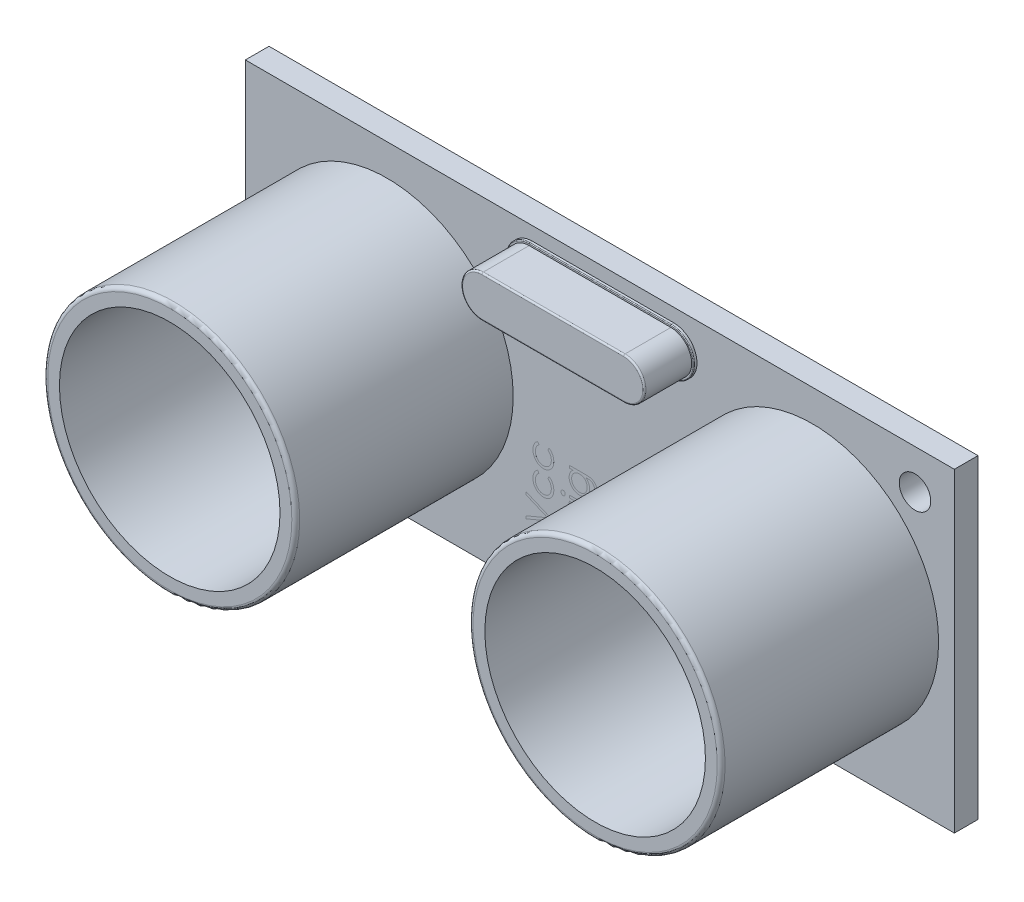
SolidWorks part; units mm, degrees
ref_plane "Front Plane" through (0, 0, 0) normal (0, 0, 1) x (1, 0, 0)
ref_plane "Top Plane" through (0, 0, 0) normal (0, 1, 0) x (1, 0, 0)
ref_plane "Right Plane" through (0, 0, 0) normal (1, 0, 0) x (0, 0, -1)
sketch "Sketch1" plane through (0, 0, 0) normal (0, 0, 1) x (1, 0, 0)
  line L1 (0, 0) -> (45, 0)
  line L2 (0, 0) -> (0, 20)
  line L3 (0, 20) -> (45, 20)
  line L4 (45, 0) -> (45, 20)
  circle A0 centre (2.5, 2.5) radius 1
  circle A1 centre (42.5, 17.5) radius 1
  dimension "D3" = 2
  dimension "D4" = 2
  dimension "D5" = 15
  dimension "D6" = 2.5
  dimension "D7" = 2.5
  dimension "D8" = 40
  dimension "D1" = 20
  dimension "D2" = 45
extrude "Boss-Extrude1" add sketch "Sketch1" along normal blind 1.5
sketch "Sketch2" plane through (0, 0, 1.5) normal (0, 0, 1) x (1, 0, 0)
  line L0 (0, 20) -> (0, 0) construction
  line L1 (45, 20) -> (0, 20) construction
  circle A0 centre (9, 10) radius 8
  circle A1 centre (36, 10) radius 8
  dimension "D1" = 16
  dimension "D2" = 16
  dimension "D3" = 27
  dimension "D4" = 9
  dimension "D5" = 10
  dimension "D6" = 10
extrude "Boss-Extrude2" add sketch "Sketch2" along normal blind 13.8
sketch "Sketch3" plane through (0, 0, 15.3) normal (0, 0, 1) x (1, 0, 0)
  circle A0 centre (9, 10) radius 7
  circle A1 centre (36, 10) radius 7
  circle A2 centre (36, 10) radius 8 construction
  dimension "D1" = 14
  dimension "D2" = 14
  dimension "D3" = 0
extrude "Cut-Extrude1" cut sketch "Sketch3" against normal blind 11
sketch "Sketch4" plane through (0, 0, 4.3) normal (0, 0, 1) x (1, 0, 0)
  circle A0 centre (9, 10) radius 6
  circle A1 centre (36, 10) radius 6
  circle A2 centre (36, 10) radius 7 construction
  dimension "D1" = 12
  dimension "D2" = 12
  dimension "D3" = 0
extrude "Boss-Extrude3" add sketch "Sketch4" along normal blind 1
fillet "Fillet1" radius 0.25 2 edges at (44, 10, 15.3) (17, 10, 15.3)
sketch "Sketch6" plane through (0, 0, 1.5) normal (0, 0, 1) x (1, 0, 0)
  line L0 (18.2127, 17.6702) -> (27.1892, 17.6702) construction
  line L1 (18.2127, 19.1439) -> (27.1892, 19.1439)
  line L2 (18.2127, 16.1964) -> (27.1892, 16.1964)
  arc A0 (18.2127, 19.1439) -> (18.2127, 16.1964) centre (18.2127, 17.6702) ccw
  arc A1 (27.1892, 16.1964) -> (27.1892, 19.1439) centre (27.1892, 17.6702) ccw
  point P2 (22.701, 17.6702)
extrude "Boss-Extrude4" add sketch "Sketch6" along normal blind 0.2
sketch "Sketch7" plane through (0, 0, 1.7) normal (0, 0, 1) x (1, 0, 0)
  line L0 (18.2101, 17.6795) -> (27.2081, 17.6795) construction
  line L1 (18.2101, 18.9989) -> (27.2081, 18.9989)
  line L2 (18.2101, 16.3602) -> (27.2081, 16.3602)
  arc A0 (18.2101, 18.9989) -> (18.2101, 16.3602) centre (18.2101, 17.6795) ccw
  arc A1 (27.2081, 16.3602) -> (27.2081, 18.9989) centre (27.2081, 17.6795) ccw
  point P2 (22.7091, 17.6795)
extrude "Boss-Extrude5" add sketch "Sketch7" along normal blind 3
fillet "Fillet2" radius 0.1 4 edges at (16.8908, 17.6795, 4.7) (22.7091, 18.9989, 4.7) (28.5274, 17.6795, 4.7) (22.7091, 16.3602, 4.7)
fillet "Fillet3" radius 0.05 4 edges at (28.6629, 17.6702, 1.7) (22.701, 16.1964, 1.7) (16.739, 17.6702, 1.7) (22.701, 19.1439, 1.7)
sketch "Sketch9" plane through (0, 0, 0) normal (0, 0, -1) x (-1, 0, 0)
  line L1 (0, 0) -> (-45, 0) construction
  circle A0 centre (-26.31, 2.5) radius 0.635
  circle A1 centre (-23.77, 2.5) radius 0.635
  circle A2 centre (-21.23, 2.5) radius 0.635
  circle A3 centre (-18.69, 2.5) radius 0.635
  point P10 (-22.5, 0)
  dimension "D1" = 1.27
  dimension "D2" = 1.27
  dimension "D3" = 1.27
  dimension "D4" = 1.27
  dimension "D5" = 2.5
  dimension "D6" = 2.54
  dimension "D7" = 2.54
  dimension "D8" = 2.54
  dimension "D9" = 2.5
  dimension "D10" = 2.5
  dimension "D11" = 2.5
  dimension "D12" = 1.27
extrude "Boss-Extrude6" add sketch "Sketch9" along normal blind 4 and the other way blind 2
sketch "Sketch10" plane through (0, 0, 1.5) normal (0, 0, 1) x (1, 0, 0)
  line L0 (19.5534, 3.5859) -> (19.5534, 8.1823) construction
  line L1 (21.8515, 8.1823) -> (21.8515, 3.5859) construction
  line L2 (24.4945, 8.1823) -> (24.4945, 3.5859) construction
  line L3 (27.0991, 8.1823) -> (27.0991, 3.5859) construction
  text T0 "Vcc" font "Century Gothic" height 1.75
  text T1 "Trig" font "Century Gothic" height 1.75
  text T2 "Echo" font "Century Gothic" height 1.75
  text T3 "GND" font "Century Gothic" height 1.75
extrude "Boss-Extrude7" add sketch "Sketch10" along normal blind 0.0001
